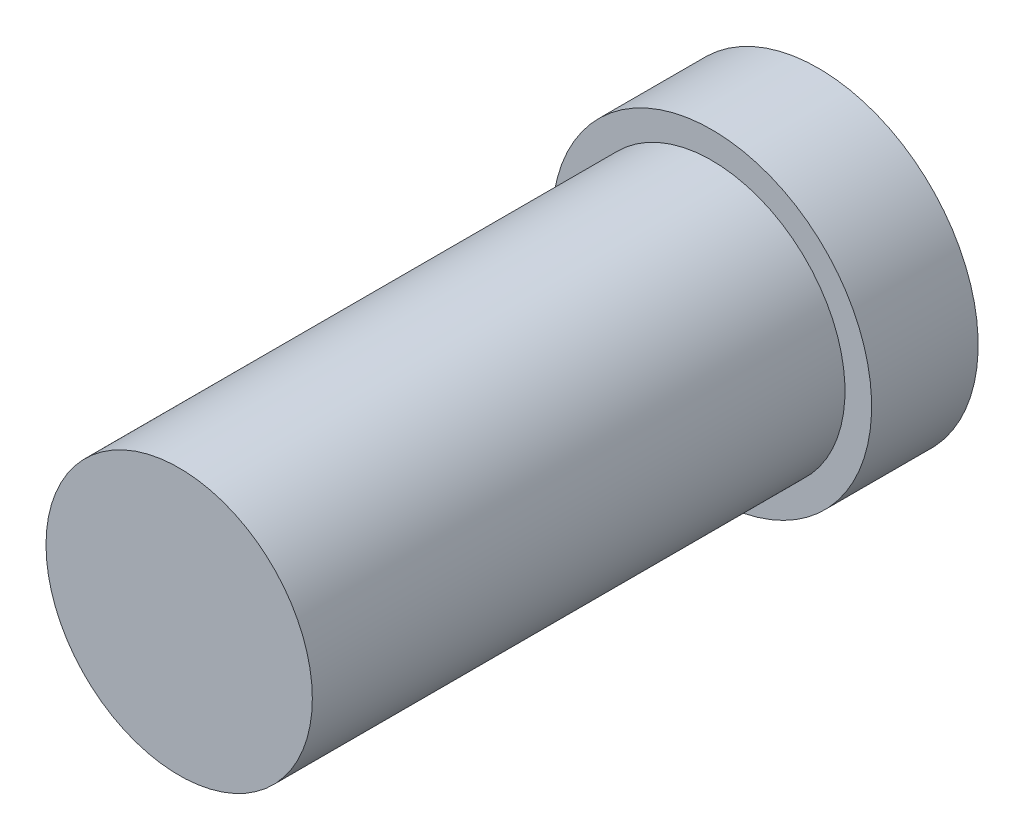
SolidWorks part; units mm, degrees
ref_plane "Front" through (0, 0, 0) normal (0, 0, 1) x (1, 0, 0)
ref_plane "Top" through (0, 0, 0) normal (0, 1, 0) x (1, 0, 0)
ref_plane "Right" through (0, 0, 0) normal (1, 0, 0) x (0, 0, -1)
sketch "Çizim1" plane through (0, 0, 0) normal (0, 0, 1) x (1, 0, 0)
  circle A0 centre (0, 0) radius 2.5
extrude "Yükseklik-Ekstrüzyon1" add sketch "Çizim1" along normal blind 10
sketch "Çizim2" plane through (0, 0, 0) normal (0, 0, -1) x (-1, 0, 0)
  circle A0 centre (0, 0) radius 3
extrude "Yükseklik-Ekstrüzyon2" add sketch "Çizim2" along normal blind 2
